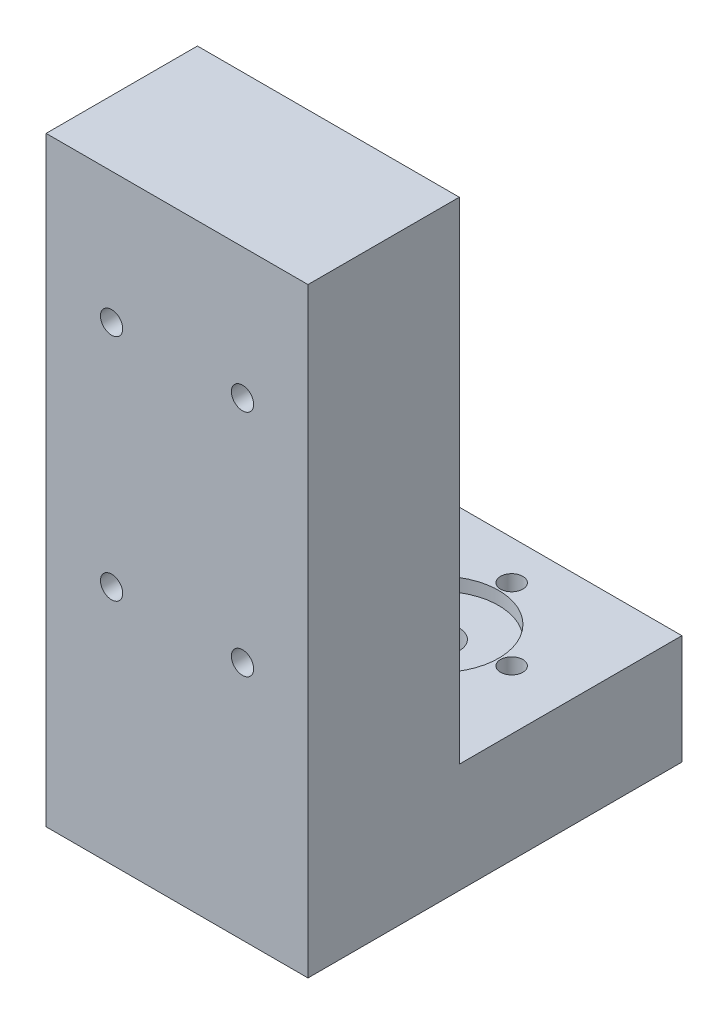
SolidWorks part; units mm, degrees
material "ABS"
ref_plane "Front Plane" through (0, 0, 0) normal (0, 0, 1) x (1, 0, 0)
ref_plane "Top Plane" through (0, 0, 0) normal (0, 1, 0) x (1, 0, 0)
ref_plane "Right Plane" through (0, 0, 0) normal (1, 0, 0) x (0, 0, -1)
sketch "Sketch1" plane through (0, 0, 0) normal (1, 0, 0) x (0, 0, -1)
  line L0 (0, 0) -> (34, 0)
  line L1 (34, 0) -> (34, -16.729)
  line L2 (34, -16.729) -> (-23.1124, -16.729)
  line L3 (-23.1124, -16.729) -> (-23.1124, 75)
  line L4 (-23.1124, 75) -> (0, 75)
  line L5 (0, 75) -> (0, 0)
  dimension "D1" = 34
  dimension "D2" = 16.729
  dimension "D3" = 75
  dimension "D4" = 23.1124
extrude "Boss-Extrude1" add sketch "Sketch1" along normal mid plane 40
sketch "Sketch3" plane through (0, 0, 0) normal (0, 1, 0) x (1, 0, 0)
  line L0 (-20, 34) -> (-20, 0) construction
  circle A0 centre (0, 17) radius 3
  point P7 (-20, 17)
  dimension "D1" = 6
extrude "Cut-Extrude2" cut sketch "Sketch3" against normal up to surface and the other way through all
sketch "Sketch2" plane through (0, 0, 0) normal (0, 1, 0) x (1, 0, 0)
  line L0 (-20, 34) -> (-20, 0) construction
  circle A0 centre (0, 17) radius 9
  point P4 (-20, 17)
  dimension "D1" = 18
extrude "Cut-Extrude1" cut sketch "Sketch2" against normal blind 2
sketch "Sketch5" plane through (0, 0, 0) normal (0, 1, 0) x (1, 0, 0)
  circle A0 centre (0, 17) radius 11 construction
  circle A1 centre (0, 28) radius 1.7
  dimension "D1" = 22
  dimension "D2" = 3.4
extrude "Cut-Extrude3" cut sketch "Sketch5" against normal up to surface (16.729 mm away) contours A1 up to face at (0, -16.729, -14)
pattern_circular "CirPattern1" count 4 every 90 about axis through (0, 0, -17) along (0, 1, 0) of "Cut-Extrude3"
sketch "Sketch6" plane through (0, 0, 0) normal (0, 0, -1) x (-1, 0, 0)
  line L0 (-20, 75) -> (20, 75) construction
  line L1 (20, 0) -> (20, 75) construction
  circle A1 centre (10, 55) radius 1.7
  dimension "D2" = 3.4
  dimension "D6" = 20
  dimension "D7" = 10
extrude "Cut-Extrude4" cut sketch "Sketch6" against normal up to surface (23.1124 mm away) contours A1 up to face at (0, 29.1355, 23.1124)
pattern_linear "LPattern1" count 2 spacing 20 along (1, 0, 0) count 2 spacing 35 along (0, -1, 0) of "Cut-Extrude4"
equation "\"defl\"= 0.3'M"
equation "\"M\"= 5400"
equation "\"L\"= 34"
equation "\"b\"= 40"
equation "\"E\"= 2000"
equation "\"SF\"= 3"
equation "\"Sy\"= 40"
equation "\"h\"= ( ( 6 * \"M\" * \"L\" * \"L\" * \"SF\" ) / ( \"E\" * \"defl\" * \"b\" ) ) ^ ( 1 / 3 )"
equation "\"L2\"= 38"
equation "\"M2\"= 11400"
equation "\"t\"= ( ( 6 * \"M2\" * \"L2\" * \"L2\" * \"SF\" ) / ( \"E\" * \"defl\" * \"b\" ) ) ^ ( 1 / 3 )"
equation "\"D2@Sketch1\"=\"h\""
equation "\"D4@Sketch1\"=\"t\""
